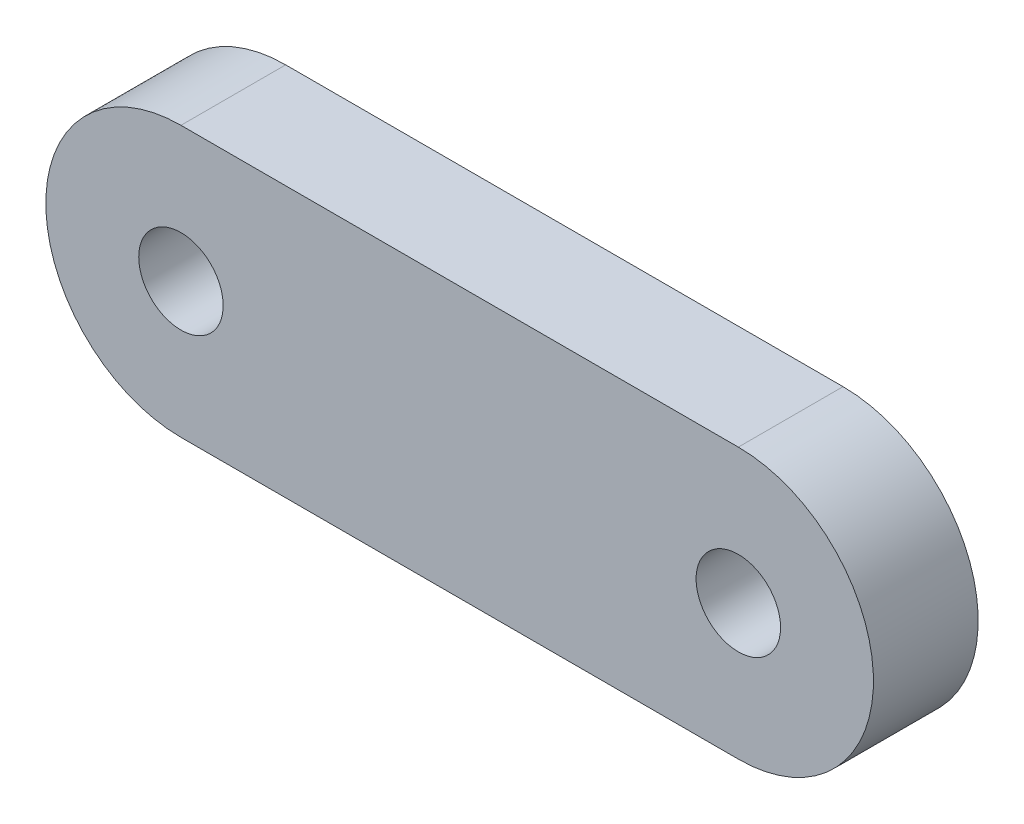
SolidWorks part; units mm, degrees
ref_plane "Front Plane" through (0, 0, 0) normal (0, 0, 1) x (1, 0, 0)
ref_plane "Top Plane" through (0, 0, 0) normal (0, 1, 0) x (1, 0, 0)
ref_plane "Right Plane" through (0, 0, 0) normal (1, 0, 0) x (0, 0, -1)
sketch "Sketch1" plane through (0, 0, 0) normal (0, 0, 1) x (1, 0, 0)
  line L0 (0, 0) -> (33, 0) construction
  line L1 (0, 8) -> (33, 8)
  line L2 (0, -8) -> (33, -8)
  arc A0 (0, 8) -> (0, -8) centre (0, 0) ccw
  arc A1 (33, -8) -> (33, 8) centre (33, 0) ccw
  circle A2 centre (0, 0) radius 2.5
  point P3 (16.5, 0)
  dimension "D2" = 8
  dimension "D3" = 5
  dimension "D1" = 33
extrude "Boss-Extrude1" add sketch "Sketch1" along normal blind 6.2
sketch "Sketch2" plane through (0, 0, 6.2) normal (0, 0, 1) x (1, 0, 0)
  circle A0 centre (33, 0) radius 2.5
  dimension "D1" = 5
extrude "Cut-Extrude1" cut sketch "Sketch2" against normal blind 16.2
